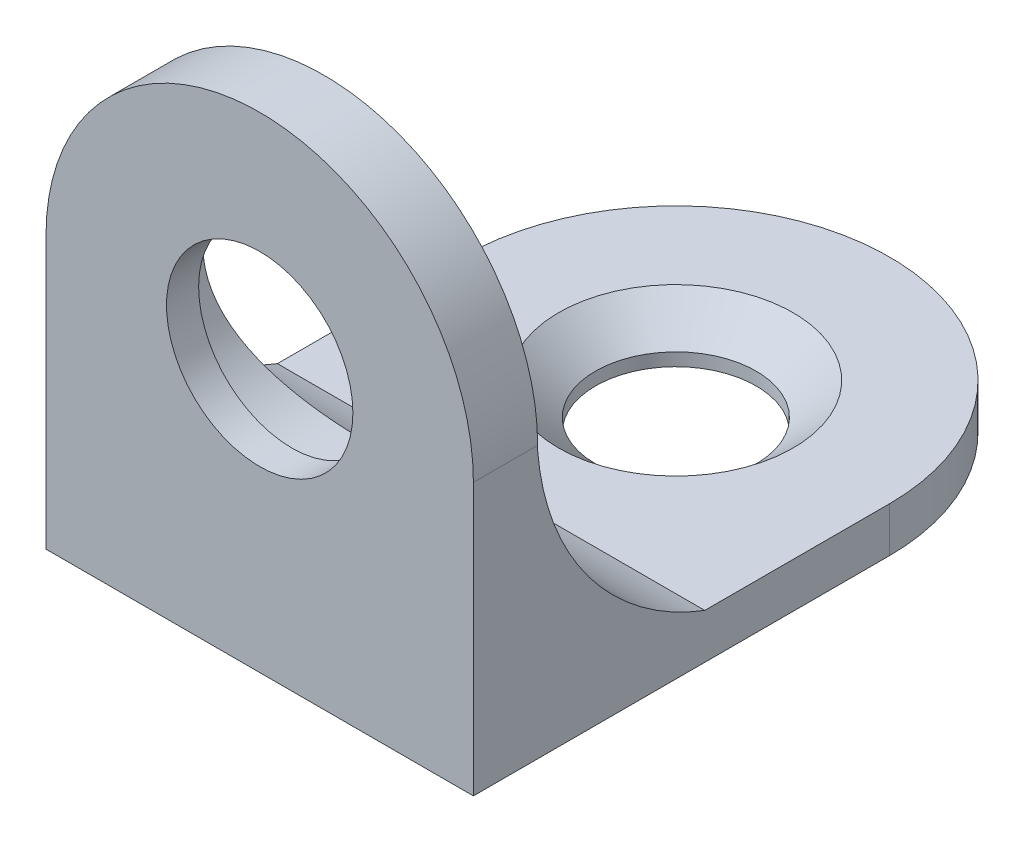
SolidWorks part; units mm, degrees
ref_plane "Plan de face" through (0, 0, 0) normal (0, 0, 1) x (1, 0, 0)
ref_plane "Plan de dessus" through (0, 0, 0) normal (0, 1, 0) x (1, 0, 0)
ref_plane "Plan de droite" through (0, 0, 0) normal (1, 0, 0) x (0, 0, -1)
sketch "Esquisse1" plane through (0, 0, 0) normal (0, 0, 1) x (1, 0, 0)
  line L0 (0, 0) -> (0, 3.3497) construction
  line L1 (-6.65, 8.45) -> (6.65, 8.45) construction
  line L2 (-6.65, 8.45) -> (-6.65, 0)
  line L3 (-6.65, 0) -> (6.65, 0)
  line L4 (6.65, 8.45) -> (6.65, 0)
  arc A0 (6.65, 8.45) -> (-6.65, 8.45) centre (0, 8.45) ccw
  circle A1 centre (0, 8.45) radius 2.9
  point P9 (0, 15.1)
  dimension "D3" = 5.8
  dimension "D1" = 13.3
  dimension "D2" = 15.1
extrude "Boss.-Extru.3" add sketch "Esquisse1" against normal blind 2
sketch "Esquisse4" plane through (0, 0, 0) normal (0, 1, 0) x (1, 0, 0)
  line L0 (0, 0) -> (0, 3.351) construction
  line L1 (6.65, 0) -> (-6.65, 0)
  line L2 (6.65, 0) -> (6.65, 12.95)
  line L3 (6.65, 12.95) -> (-6.65, 12.95) construction
  line L4 (-6.65, 0) -> (-6.65, 12.95)
  arc A0 (6.65, 12.95) -> (-6.65, 12.95) centre (0, 12.95) ccw
  circle A1 centre (0, 12.95) radius 2.5
  point P10 (0, 19.6)
  dimension "D2" = 5
  dimension "D1" = 19.6
extrude "Boss.-Extru.4" add sketch "Esquisse4" along normal blind 1.4
sketch "Esquisse5" plane through (-6.65, 0, 0) normal (-1, 0, 0) x (0, 0, 1)
  line L0 (0, 0) -> (-1.2107, 1.2107) construction
  line L1 (0, 8.45) -> (0, 0) construction
  line L2 (-2, 8.45) -> (-2, 1.4) construction
  line L3 (-12.95, 0) -> (0, 0) construction
  line L4 (-12.95, 1.4) -> (-2, 1.4) construction
  line L5 (-2, 8.45) -> (-2, 1.4)
  line L6 (-7.2, 1.4) -> (-2, 1.4)
  arc A0 (-7.2, 1.4) -> (-2, 8.3) centre (-10.0479, 8.9556) ccw
  point P0 (-3.8184, 3.8184)
  point P6 (-2, 8.3)
  point P12 (-7.2, 1.4)
  line M2 (-2, 8.45) -> (-2, 1.4)
  line M3 (-2, 1.4) -> (-12.95, 1.4)
  dimension "D1" = 5.4
  dimension "D2" = 45
  dimension "D3" = 8.3
  dimension "D4" = 7.2
extrude "Boss.-Extru.5" add sketch "Esquisse5" against normal up to surface (13.3 mm away) contours L0 A0 M2 M3 | L0 L5 A0
sketch "Esquisse6" plane through (0, 0, -2) normal (0, 0, -1) x (-1, 0, 0)
  circle A0 centre (0, 8.45) radius 3.75
  arc A4 (2.8961, 8.3) -> (-2.8961, 8.3) centre (0, 8.45) ccw construction
  dimension "D1" = 7.5
extrude "Enlèv. mat.-Extru.2" cut sketch "Esquisse6" against normal blind 1
sketch "Esquisse7" plane through (0, 0, -1) normal (0, 0, -1) x (-1, 0, 0)
  circle A0 centre (0, 8.45) radius 3.75 construction
  circle A1 centre (0, 8.45) radius 3.75
extrude "Enlèv. mat.-Extru.3" cut sketch "Esquisse7" along normal through all
sketch "Esquisse8" plane through (0, 1.4, 0) normal (0, 1, 0) x (1, 0, 0)
  circle A0 centre (0, 12.95) radius 3.65
  circle A1 centre (0, 12.95) radius 2.5 construction
  dimension "D1" = 7.3
ref_plane "Plan1" through (0, 0.4, 0) normal (0, 1, 0) x (1, 0, 0)
sketch "Esquisse9" plane through (0, 0.4, 0) normal (0, 1, 0) x (1, 0, 0)
  circle A0 centre (0, 12.95) radius 2.5
  circle A1 centre (0, 12.95) radius 2.5 construction
loft "Enlèvement de matière-Lissage1" cut profiles "Esquisse9", "Esquisse8"
